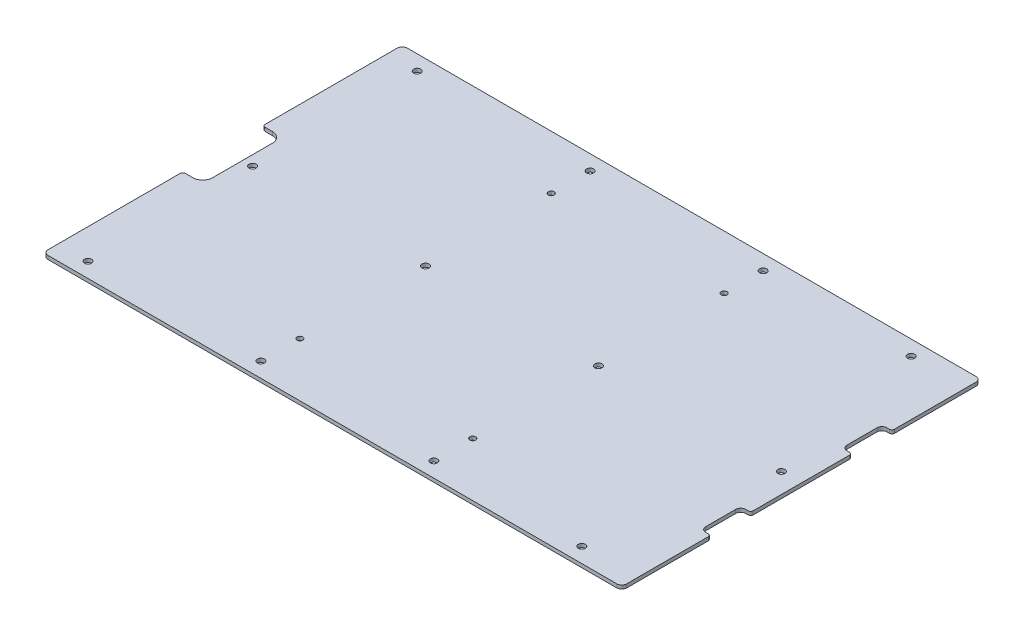
SolidWorks part; units mm, degrees
material "1060 Alloy"
ref_plane "Front" through (0, 0, 0) normal (0, 0, 1) x (1, 0, 0)
ref_plane "Top" through (0, 0, 0) normal (0, 1, 0) x (1, 0, 0)
ref_plane "Right" through (0, 0, 0) normal (1, 0, 0) x (0, 0, -1)
sketch "Sketch1" plane through (0, 0, 0) normal (0, 1, 0) x (1, 0, 0)
  line L0 (-55.0333, 0) -> (-165.1, 0) construction
  line L1 (-180.975, 114.3) -> (180.975, 114.3)
  line L2 (-184.15, 111.125) -> (-184.15, -111.125)
  line L3 (-180.975, -114.3) -> (180.975, -114.3)
  line L4 (184.15, 111.125) -> (184.15, -111.125)
  line L5 (-184.15, 114.3) -> (184.15, -114.3) construction
  line L6 (-184.15, -114.3) -> (184.15, 114.3) construction
  line L7 (-165.1, -104.775) -> (165.1, -104.775) construction
  line L8 (-165.1, -104.775) -> (-165.1, 104.775) construction
  line L9 (-165.1, 104.775) -> (165.1, 104.775) construction
  line L10 (165.1, -104.775) -> (165.1, 104.775) construction
  line L11 (-165.1, -104.775) -> (165.1, 104.775) construction
  line L12 (-165.1, 104.775) -> (165.1, -104.775) construction
  line L13 (-55.0333, -104.775) -> (55.0333, -104.775) construction
  line L14 (-55.0333, -104.775) -> (-55.0333, 104.775) construction
  line L15 (-55.0333, 104.775) -> (55.0333, 104.775) construction
  line L16 (55.0333, -104.775) -> (55.0333, 104.775) construction
  line L17 (-55.0333, -104.775) -> (55.0333, 104.775) construction
  line L18 (-55.0333, 104.775) -> (55.0333, -104.775) construction
  line L19 (55.0333, 0) -> (165.1, 0) construction
  line L20 (-55.0333, 0) -> (55.0333, 0) construction
  line L31 (-55.0291, 80.01) -> (55.0291, 80.01) construction
  line L32 (149.225, -104.775) -> (149.225, 104.775) construction
  line L33 (-55.0291, 80.01) -> (-55.0291, -80.01) construction
  line L34 (-55.0291, -80.01) -> (55.0291, -80.01) construction
  line L35 (55.0291, 80.01) -> (55.0291, -80.01) construction
  line L36 (-55.0291, 80.01) -> (55.0291, -80.01) construction
  line L37 (-55.0291, -80.01) -> (55.0291, 80.01) construction
  circle A0 centre (-165.1, 104.775) radius 2.2479
  circle A1 centre (-55.0333, 104.775) radius 2.2479
  circle A2 centre (55.0333, 104.775) radius 2.2479
  circle A3 centre (165.1, 104.775) radius 2.2479 construction
  circle A4 centre (165.1, -104.775) radius 2.2479 construction
  circle A5 centre (55.0333, -104.775) radius 2.2479
  circle A6 centre (-55.0333, -104.775) radius 2.2479
  circle A7 centre (-165.1, -104.775) radius 2.2479
  circle A12 centre (-55.0333, 0) radius 2.2479
  circle A13 centre (55.0333, 0) radius 2.2479
  arc A14 (184.15, 111.125) -> (180.975, 114.3) centre (180.975, 111.125) ccw
  arc A15 (184.15, -111.125) -> (180.975, -114.3) centre (180.975, -111.125) cw
  arc A16 (-180.975, -114.3) -> (-184.15, -111.125) centre (-180.975, -111.125) cw
  arc A17 (-180.975, 114.3) -> (-184.15, 111.125) centre (-180.975, 111.125) ccw
  circle A24 centre (149.225, -104.775) radius 2.2479
  circle A25 centre (149.225, 104.775) radius 2.2479
  circle A26 centre (55.0291, -80.01) radius 1.8288
  circle A27 centre (-55.0291, -80.01) radius 1.8288
  circle A28 centre (-55.0291, 80.01) radius 1.8288
  circle A29 centre (55.0291, 80.01) radius 1.8288
  circle A30 centre (171.45, 0) radius 2.2479
  circle A31 centre (-165.1, 0) radius 2.2479
  point P0 (0, 0)
  point P6 (0, 0)
  point P11 (0, 0)
  point P28 (0, 0)
  point P29 (0, 0)
  point P32 (0, 0)
  dimension "D5" = 4.4958
  dimension "D8" = 3.6576
  dimension "D11" = 3.175
  dimension "D10" = 12.7
  dimension "D12" = 19.05
  dimension "D13" = 110.0667
  dimension "D1" = 368.3
  dimension "D2" = 228.6
  dimension "D3" = 9.525
  dimension "D4" = 19.05
  dimension "D6" = 160.02
  dimension "D7" = 34.925
  dimension "D9" = 110.0582
extrude "Boss-Extrude1" add sketch "Sketch1" along normal blind 2.286
sketch "Sketch2" plane through (0, 0, 0) normal (0, -1, 0) x (1, 0, 0)
  line L5 (184.15, 111.125) -> (184.15, -111.125) construction
  line L6 (184.15, 57.658) -> (180.975, 57.658)
  line L7 (184.15, 57.658) -> (184.15, 32.258)
  line L8 (184.15, 32.258) -> (180.975, 32.258)
  line L9 (177.8, 54.483) -> (177.8, 35.433)
  line L10 (-184.15, 0) -> (183.134, 0) construction
  line L11 (-184.15, -111.125) -> (-184.15, 111.125) construction
  line L12 (183.134, -115.824) -> (183.134, 115.824) construction
  line L13 (177.8, 44.958) -> (184.15, 44.958) construction
  line L14 (184.15, -32.258) -> (180.975, -32.258)
  line L15 (184.15, -57.658) -> (184.15, -32.258)
  line L16 (177.8, -54.483) -> (177.8, -35.433)
  line L17 (184.15, -57.658) -> (180.975, -57.658)
  line L19 (-184.15, 25.4) -> (-177.8, 25.4)
  line L20 (-184.15, 25.4) -> (-184.15, -25.4)
  line L21 (-184.15, -25.4) -> (-177.8, -25.4)
  line L22 (-171.45, 19.05) -> (-171.45, -19.05)
  arc A0 (180.975, -57.658) -> (177.8, -54.483) centre (180.975, -54.483) cw
  arc A1 (177.8, -35.433) -> (180.975, -32.258) centre (180.975, -35.433) cw
  arc A2 (177.8, 35.433) -> (180.975, 32.258) centre (180.975, 35.433) ccw
  arc A3 (177.8, 54.483) -> (180.975, 57.658) centre (180.975, 54.483) cw
  arc A4 (-171.45, -19.05) -> (-177.8, -25.4) centre (-177.8, -19.05) cw
  arc A5 (-171.45, 19.05) -> (-177.8, 25.4) centre (-177.8, 19.05) ccw
  point P20 (177.8, -57.658)
  point P23 (177.8, -32.258)
  point P26 (177.8, 32.258)
  point P29 (177.8, 57.658)
  point P38 (-171.45, 25.4)
  dimension "D4" = 3.175
  dimension "D7" = 6.35
  dimension "D1" = 25.4
  dimension "D2" = 44.958
  dimension "D3" = 6.35
  dimension "D5" = 50.8
  dimension "D6" = 12.7
extrude "Cut-Extrude1" cut sketch "Sketch2" against normal through all
fillet "Fillet1" radius 1.5875 6 edges at (184.15, 1.143, -57.658) (184.15, 1.143, -32.258) (184.15, 1.143, 32.258) (184.15, 1.143, 57.658) (-184.15, 1.143, -25.4) (-184.15, 1.143, 25.4)
